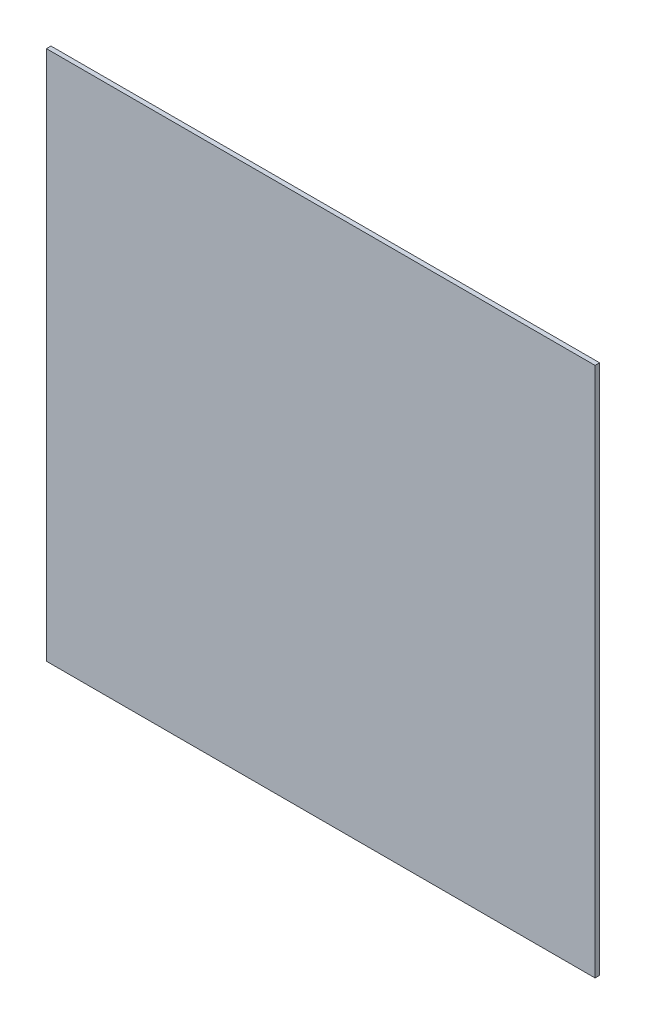
SolidWorks part; units mm, degrees
ref_plane "Plan de face" through (0, 0, 0) normal (0, 0, 1) x (1, 0, 0)
ref_plane "Plan de dessus" through (0, 0, 0) normal (0, 1, 0) x (1, 0, 0)
ref_plane "Plan de droite" through (0, 0, 0) normal (1, 0, 0) x (0, 0, -1)
sketch "Esquisse1" plane through (0, 0, 0) normal (0, 0, 1) x (1, 0, 0)
  line L1 (-302.5, 292.5) -> (302.5, 292.5)
  line L2 (-302.5, 292.5) -> (-302.5, -292.5)
  line L3 (-302.5, -292.5) -> (302.5, -292.5)
  line L4 (302.5, 292.5) -> (302.5, -292.5)
  line L5 (-302.5, 292.5) -> (302.5, -292.5) construction
  line L6 (-302.5, -292.5) -> (302.5, 292.5) construction
  point P0 (0, 0)
  dimension "D1" = 605
  dimension "D2" = 585
extrude "Boss.-Extru.1" add sketch "Esquisse1" along normal blind 5
